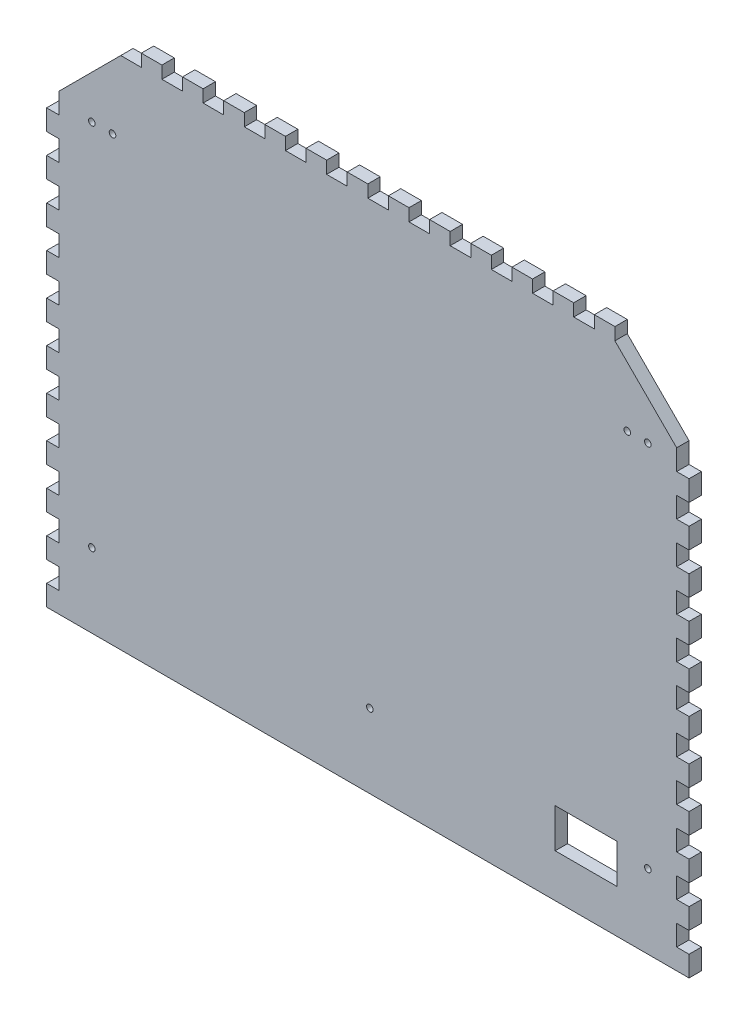
SolidWorks part; units mm, degrees
material "Buche"
ref_plane "Ebene vorne" through (0, 0, 0) normal (0, 0, 1) x (1, 0, 0)
ref_plane "Ebene oben" through (0, 0, 0) normal (0, 1, 0) x (1, 0, 0)
ref_plane "Ebene rechts" through (0, 0, 0) normal (1, 0, 0) x (0, 0, -1)
sketch "Skizze1" plane through (0, 0, 0) normal (0, 0, 1) x (1, 0, 0)
  line L0 (4, 10) -> (4, 20)
  line L1 (4, 0) -> (304, 0)
  line L2 (304, 10) -> (304, 20)
  line L3 (54, 250) -> (64, 250)
  line L4 (4, 220) -> (34, 250)
  line L5 (304, 220) -> (274, 250)
  line L6 (34, 250) -> (44, 250)
  line L7 (44, 250) -> (44, 256)
  line L8 (44, 256) -> (54, 256)
  line L9 (54, 256) -> (54, 250)
  line L10 (64, 250) -> (64, 256)
  line L11 (64, 256) -> (74, 256)
  line L12 (74, 256) -> (74, 250)
  line L13 (304, 0) -> (310, 0)
  line L14 (310, 0) -> (310, 10)
  line L15 (310, 10) -> (304, 10)
  line L16 (304, 30) -> (304, 40)
  line L17 (304, 20) -> (310, 20)
  line L18 (310, 20) -> (310, 30)
  line L19 (310, 30) -> (304, 30)
  line L20 (304, 40) -> (310, 40)
  line L21 (304, 50) -> (304, 60)
  line L22 (310, 40) -> (310, 50)
  line L23 (310, 50) -> (304, 50)
  line L24 (304, 60) -> (310, 60)
  line L25 (304, 70) -> (304, 80)
  line L26 (310, 60) -> (310, 70)
  line L27 (310, 70) -> (304, 70)
  line L28 (304, 80) -> (310, 80)
  line L29 (304, 90) -> (304, 100)
  line L30 (310, 80) -> (310, 90)
  line L31 (310, 90) -> (304, 90)
  line L32 (304, 100) -> (310, 100)
  line L33 (304, 110) -> (304, 120)
  line L34 (310, 100) -> (310, 110)
  line L35 (310, 110) -> (304, 110)
  line L36 (304, 120) -> (310, 120)
  line L37 (304, 130) -> (304, 140)
  line L38 (310, 120) -> (310, 130)
  line L39 (310, 130) -> (304, 130)
  line L40 (304, 140) -> (310, 140)
  line L41 (304, 150) -> (304, 160)
  line L42 (310, 140) -> (310, 150)
  line L43 (310, 150) -> (304, 150)
  line L44 (304, 160) -> (310, 160)
  line L45 (304, 170) -> (304, 180)
  line L46 (310, 160) -> (310, 170)
  line L47 (310, 170) -> (304, 170)
  line L48 (304, 180) -> (310, 180)
  line L49 (304, 190) -> (304, 200)
  line L50 (310, 180) -> (310, 190)
  line L51 (310, 190) -> (304, 190)
  line L52 (304, 200) -> (310, 200)
  line L53 (304, 210) -> (304, 220)
  line L54 (310, 200) -> (310, 210)
  line L55 (310, 210) -> (304, 210)
  line L56 (4, 0) -> (-2, 0)
  line L57 (-2, 0) -> (-2, 10)
  line L58 (-2, 10) -> (4, 10)
  line L59 (4, 30) -> (4, 40)
  line L60 (4, 20) -> (-2, 20)
  line L61 (-2, 20) -> (-2, 30)
  line L62 (-2, 30) -> (4, 30)
  line L63 (4, 50) -> (4, 60)
  line L64 (4, 40) -> (-2, 40)
  line L65 (-2, 40) -> (-2, 50)
  line L66 (-2, 50) -> (4, 50)
  line L67 (4, 70) -> (4, 80)
  line L68 (4, 60) -> (-2, 60)
  line L69 (-2, 60) -> (-2, 70)
  line L70 (-2, 70) -> (4, 70)
  line L71 (4, 90) -> (4, 100)
  line L72 (4, 80) -> (-2, 80)
  line L73 (-2, 80) -> (-2, 90)
  line L74 (-2, 90) -> (4, 90)
  line L75 (4, 110) -> (4, 120)
  line L76 (4, 100) -> (-2, 100)
  line L77 (-2, 100) -> (-2, 110)
  line L78 (-2, 110) -> (4, 110)
  line L79 (4, 130) -> (4, 140)
  line L80 (4, 120) -> (-2, 120)
  line L81 (-2, 120) -> (-2, 130)
  line L82 (-2, 130) -> (4, 130)
  line L83 (4, 150) -> (4, 160)
  line L84 (4, 140) -> (-2, 140)
  line L85 (-2, 140) -> (-2, 150)
  line L86 (-2, 150) -> (4, 150)
  line L87 (4, 170) -> (4, 180)
  line L88 (4, 160) -> (-2, 160)
  line L89 (-2, 160) -> (-2, 170)
  line L90 (-2, 170) -> (4, 170)
  line L91 (4, 190) -> (4, 200)
  line L92 (4, 180) -> (-2, 180)
  line L93 (-2, 180) -> (-2, 190)
  line L94 (-2, 190) -> (4, 190)
  line L95 (4, 210) -> (4, 220)
  line L96 (4, 200) -> (-2, 200)
  line L97 (-2, 200) -> (-2, 210)
  line L98 (-2, 210) -> (4, 210)
  line L99 (74, 250) -> (84, 250)
  line L100 (84, 250) -> (84, 256)
  line L101 (84, 256) -> (94, 256)
  line L102 (94, 256) -> (94, 250)
  line L103 (94, 250) -> (104, 250)
  line L104 (104, 250) -> (104, 256)
  line L105 (104, 256) -> (114, 256)
  line L106 (114, 256) -> (114, 250)
  line L107 (114, 250) -> (124, 250)
  line L108 (124, 250) -> (124, 256)
  line L109 (124, 256) -> (134, 256)
  line L110 (134, 256) -> (134, 250)
  line L111 (134, 250) -> (144, 250)
  line L112 (144, 250) -> (144, 256)
  line L113 (144, 256) -> (154, 256)
  line L114 (154, 256) -> (154, 250)
  line L115 (154, 250) -> (164, 250)
  line L116 (164, 250) -> (164, 256)
  line L117 (164, 256) -> (174, 256)
  line L118 (174, 256) -> (174, 250)
  line L119 (174, 250) -> (184, 250)
  line L120 (184, 250) -> (184, 256)
  line L121 (184, 256) -> (194, 256)
  line L122 (194, 256) -> (194, 250)
  line L123 (194, 250) -> (204, 250)
  line L124 (204, 250) -> (204, 256)
  line L125 (204, 256) -> (214, 256)
  line L126 (214, 256) -> (214, 250)
  line L127 (214, 250) -> (224, 250)
  line L128 (224, 250) -> (224, 256)
  line L129 (224, 256) -> (234, 256)
  line L130 (234, 256) -> (234, 250)
  line L131 (234, 250) -> (244, 250)
  line L132 (244, 250) -> (244, 256)
  line L133 (244, 256) -> (254, 256)
  line L134 (254, 256) -> (254, 250)
  line L135 (254, 250) -> (264, 250)
  line L136 (264, 250) -> (264, 256)
  line L137 (264, 256) -> (274, 256)
  line L138 (274, 256) -> (274, 250)
  line L140 (245, 21) -> (275, 21)
  line L141 (245, 21) -> (245, 40)
  line L142 (245, 40) -> (275, 40)
  line L143 (275, 21) -> (275, 40)
  line L144 (304, 220) -> (310, 220) [skipped]
  circle A0 centre (20, 215) radius 1.6
  circle A1 centre (30, 215) radius 1.6
  circle A2 centre (290, 215) radius 1.6
  circle A3 centre (280, 215) radius 1.6
  circle A4 centre (20, 36) radius 1.6
  circle A5 centre (155, 36) radius 1.6
  circle A6 centre (290, 36) radius 1.6
  dimension "D2" = 11
  dimension "D1" = 12
  dimension "D3" = 6
  dimension "D4" = 6
  dimension "D5" = 11
  dimension "D6" = 30
  dimension "D7" = 312
  dimension "D8" = 6
  dimension "D9" = 30
  dimension "D10" = 30
  dimension "D11" = 30
  dimension "D12" = 300
extrude "Aufsatz-Linear austragen1" add sketch "Skizze1" along normal blind 6
